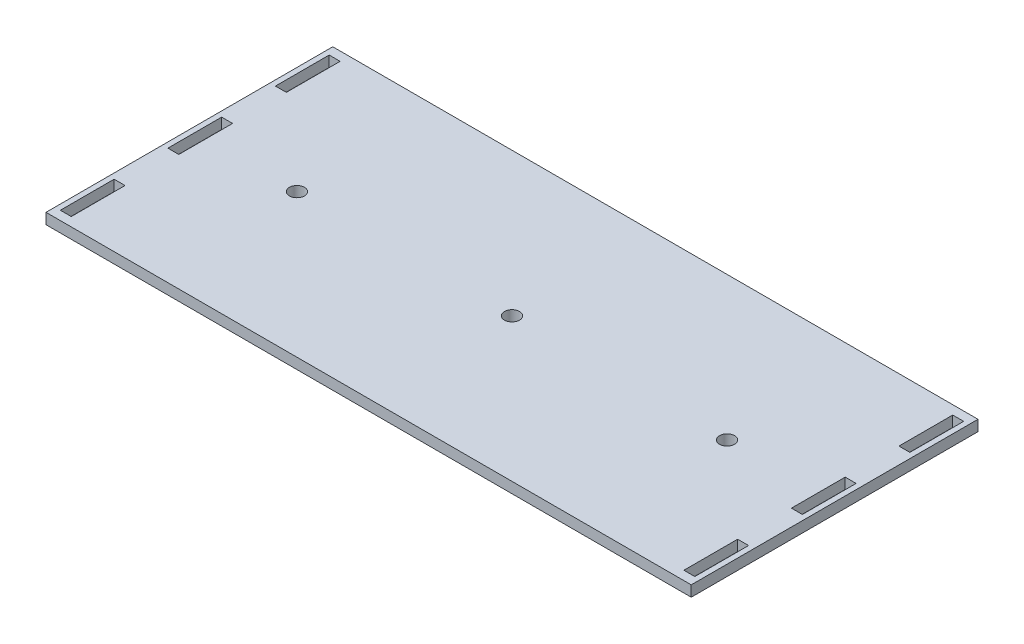
SolidWorks part; units mm, degrees
ref_plane "前视基准面" through (0, 0, 0) normal (0, 0, 1) x (1, 0, 0)
ref_plane "上视基准面" through (0, 0, 0) normal (0, 1, 0) x (1, 0, 0)
ref_plane "右视基准面" through (0, 0, 0) normal (1, 0, 0) x (0, 0, -1)
other "Configuration Table"
sketch "草图1" plane through (0, 0, 0) normal (0, 1, 0) x (1, 0, 0)
  line L0 (0, 61.0991) -> (0, -64.6496) construction
  line L1 (-90, -40) -> (90, -40)
  line L2 (-90, -40) -> (-90, 40)
  line L3 (-90, 40) -> (90, 40)
  line L4 (90, -40) -> (90, 40)
  line L5 (-90, -40) -> (90, 40) construction
  line L6 (-90, 40) -> (90, -40) construction
  line L7 (-88.5, 37.5) -> (-85.45, 37.5)
  line L8 (-88.5, 37.5) -> (-88.5, 22.5)
  line L9 (-88.5, 22.5) -> (-85.45, 22.5)
  line L10 (-85.45, 37.5) -> (-85.45, 22.5)
  line L11 (-88.5, 7.5) -> (-85.45, 7.5)
  line L12 (-88.5, 7.5) -> (-88.5, -7.5)
  line L13 (-88.5, -7.5) -> (-85.45, -7.5)
  line L14 (-85.45, 7.5) -> (-85.45, -7.5)
  line L15 (-88.5, -22.5) -> (-85.45, -22.5)
  line L16 (-88.5, -22.5) -> (-88.5, -37.5)
  line L17 (-88.5, -37.5) -> (-85.45, -37.5)
  line L18 (-85.45, -22.5) -> (-85.45, -37.5)
  line L19 (88.5, -37.5) -> (85.45, -37.5)
  line L20 (85.45, -22.5) -> (85.45, -37.5)
  line L21 (88.5, -22.5) -> (88.5, -37.5)
  line L22 (88.5, -22.5) -> (85.45, -22.5)
  line L23 (85.45, 7.5) -> (85.45, -7.5)
  line L24 (88.5, -7.5) -> (85.45, -7.5)
  line L25 (88.5, 7.5) -> (88.5, -7.5)
  line L26 (88.5, 7.5) -> (85.45, 7.5)
  line L27 (88.5, 22.5) -> (85.45, 22.5)
  line L28 (85.45, 37.5) -> (85.45, 22.5)
  line L29 (88.5, 37.5) -> (85.45, 37.5)
  line L30 (88.5, 37.5) -> (88.5, 22.5)
  line L31 (88.5, -37.5) -> (85.45, -37.5)
  line L32 (88.5, -22.5) -> (88.5, -37.5)
  line L33 (85.45, -22.5) -> (85.45, -37.5)
  line L34 (88.5, -22.5) -> (85.45, -22.5)
  line L35 (88.5, -7.5) -> (85.45, -7.5)
  line L36 (88.5, 7.5) -> (88.5, -7.5)
  line L37 (85.45, 7.5) -> (85.45, -7.5)
  line L38 (88.5, 7.5) -> (85.45, 7.5)
  line L39 (88.5, 22.5) -> (85.45, 22.5)
  line L40 (88.5, 37.5) -> (88.5, 22.5)
  line L41 (88.5, 37.5) -> (85.45, 37.5)
  line L42 (85.45, 37.5) -> (85.45, 22.5)
  line L43 (-93.4104, 0) -> (94.8742, 0) construction
  circle A0 centre (-60, 0) radius 2.1
  circle A1 centre (0, 0) radius 2.1
  circle A2 centre (60, 0) radius 2.1
  point P0 (0, 0)
  point P18 (-86.975, 7.5)
  dimension "D9" = 4.2
  dimension "D1" = 180
  dimension "D2" = 80
  dimension "D3" = 3.05
  dimension "D4" = 15
  dimension "D5" = 15
  dimension "D6" = 15
  dimension "D7" = 1.5
  dimension "D8" = 2.5
  dimension "D10" = 120
extrude "凸台-拉伸1" add sketch "草图1" along normal blind 3
